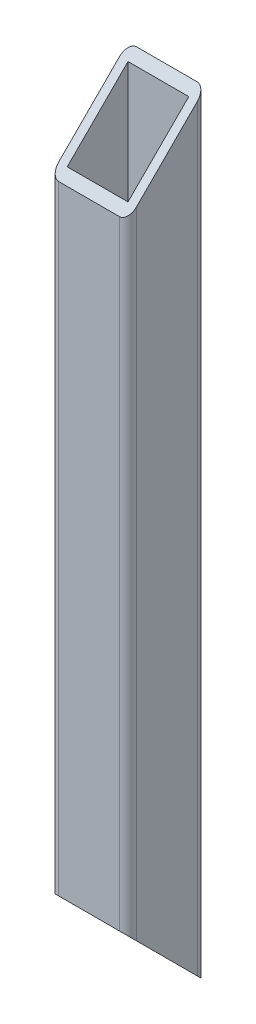
SolidWorks part; units mm, degrees
ref_plane "Front Plane" through (0, 0, 0) normal (0, 0, 1) x (1, 0, 0)
ref_plane "Top Plane" through (0, 0, 0) normal (0, 1, 0) x (1, 0, 0)
ref_plane "Right Plane" through (0, 0, 0) normal (1, 0, 0) x (0, 0, -1)
sketch "Sketch1" plane through (0, 0, 0) normal (0, 1, 0) x (1, 0, 0)
  line L1 (2.8, 0) -> (22.8, 0)
  line L2 (0, -2.8) -> (0, -22.8)
  line L3 (2.8, -25.6) -> (22.8, -25.6)
  line L4 (25.6, -2.8) -> (25.6, -22.8)
  arc A0 (22.8, 0) -> (25.6, -2.8) centre (22.8, -2.8) cw
  arc A1 (22.8, -25.6) -> (25.6, -22.8) centre (22.8, -22.8) ccw
  arc A2 (0, -22.8) -> (2.8, -25.6) centre (2.8, -22.8) ccw
  arc A3 (2.8, 0) -> (0, -2.8) centre (2.8, -2.8) ccw
  point P7 (25.6, 0)
  point P10 (25.6, -25.6)
  point P15 (0, 0)
  dimension "D2" = 2.8
  dimension "D1" = 25.6
extrude "Boss-Extrude1" add sketch "Sketch1" along normal blind 254.788
sketch "Sketch3" plane through (0, 0, 0) normal (0, -1, 0) x (-1, 0, 0)
  line L4 (-2.8, -2.8) -> (-22.8, -2.8)
  line L5 (-2.8, -2.8) -> (-2.8, -22.8)
  line L6 (-2.8, -22.8) -> (-22.8, -22.8)
  line L7 (-22.8, -2.8) -> (-22.8, -22.8)
  line L8 (-2.8, -2.8) -> (-22.8, -22.8) construction
  line L9 (-2.8, -22.8) -> (-22.8, -2.8) construction
  point P6 (-12.8, -12.8)
extrude "Cut-Extrude1" cut sketch "Sketch3" against normal blind 1040.5
ref_plane "Plane1" through (1.4, 0, 0) normal (-1, 0, 0) x (0, 0, 1)
sketch "Sketch4" plane through (1.4, 0, 0) normal (-1, 0, 0) x (0, 0, 1)
  line L0 (0, 0) -> (26.0863, 26.0863)
extrude "Cut-Extrude4" cut sketch "Sketch4" against normal through all and the other way through all flip side to cut
sketch "Sketch5" plane through (1.4, 0, 0) normal (-1, 0, 0) x (0, 0, 1)
  line L0 (0, 254.788) -> (25.6, 229.188)
extrude "Cut-Extrude8" cut sketch "Sketch5" against normal through all and the other way through all
